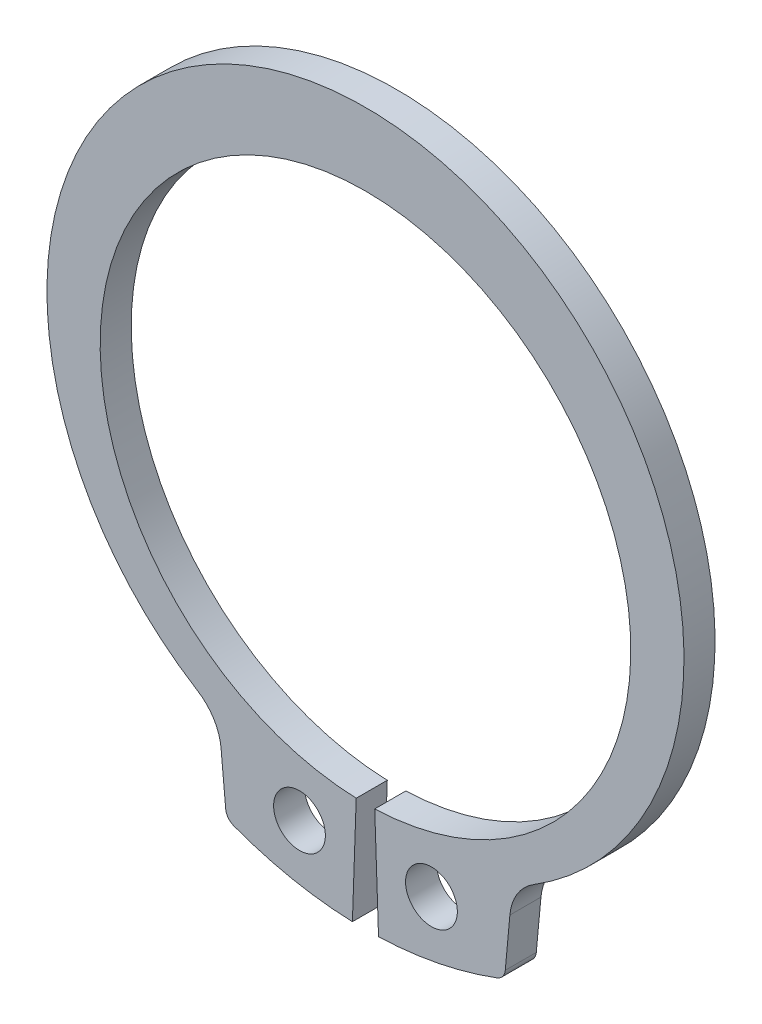
SolidWorks part; units mm, degrees
ref_plane "Front" through (0, 0, 0) normal (0, 0, 1) x (1, 0, 0)
ref_plane "Top" through (0, 0, 0) normal (0, 1, 0) x (1, 0, 0)
ref_plane "Right" through (0, 0, 0) normal (1, 0, 0) x (0, 0, -1)
sketch "Sketch1" plane through (0, 0, 0) normal (0, 0, 1) x (1, 0, 0)
  line L0 (0, 0) -> (-8.8768, -5.125) construction
  line L1 (0, 14.45) -> (0, -14.45) construction
  line L2 (-5.3727, -13.4235) -> (-5.6713, -10.1764) construction
  line L4 (-5.6713, -10.1764) -> (-6.3528, -11.3993) construction
  line L5 (-5.6713, -10.1764) -> (0, 0) construction
  line L6 (0, 10.25) -> (0, 13.05) construction
  line L7 (0, 13.05) -> (0, 11.65) construction
  line L8 (0, -10.25) -> (0, -14.45) construction
  line L9 (-2.9831, -14.1477) -> (0, 0) construction
  line L10 (0, 0) -> (-0.5046, -14.45) construction
  line L11 (-5.3727, -13.4235) -> (0, 0) construction
  line L12 (-5.5852, -11.1124) -> (-6.4883, -9.7116) construction
  line L13 (-6.0368, -10.412) -> (-5.6713, -10.1764) construction
  line L14 (-2.1148, -10.0295) -> (-2.9831, -14.1477) construction
  line L15 (-2.5489, -12.0886) -> (-1.5705, -12.2949) construction
  arc A0 (0, 13.05) -> (-5.6713, -10.1764) centre (0, 0.7444) ccw construction
  circle A2 centre (0, 0) radius 13.05 construction
  arc A3 (-5.3727, -13.4235) -> (-0.5046, -14.45) centre (0, 0) ccw construction
  circle A4 centre (0, 0) radius 10.25 construction
  circle A6 centre (-2.5489, -12.0886) radius 1 construction
  arc A7 (-6.4883, -9.7116) -> (-5.5852, -11.1124) centre (-7.5139, -11.3644) cw construction
  circle A9 centre (0, 0) radius 11 construction
  circle A10 centre (0, 0) radius 10.5 construction
  point P5 (-8.8768, -5.125)
  point P24 (-4.8492, -12.1156)
  point P35 (0, 13.05)
  point P36 (0, 10.25)
  point P37 (0, -10.25)
  point P38 (0, -14.45)
  dimension "Hole Diameter" = 2
  dimension "D10" = 1.9451
  dimension "For OD" = 22
  dimension "ID" = 20.5
  dimension "Max Sec." = 2.8
  dimension "Lug Height" = 4.2
  dimension "D6" = 2
  dimension "D5" = 3.2609
  dimension "D8" = 1.6667
  dimension "D3" = 120
  dimension "D2" = 5
  dimension "D4" = 1.6667
sketch "Sketch2" plane through (0, 0, 0) normal (-1, 0, 0) x (0, 1, 0)
  line L0 (-13.05, 0.6) -> (-13.05, -0.6) construction
  line L1 (13.05, -0.65) -> (13.05, 0.65) construction
  line L2 (0, 0.6) -> (0, -0.6) construction
  line L4 (-13.05, 0) -> (13.05, 0) construction
  point P3 (-13.05, 0)
  point P6 (0, 0)
  point P14 (13.05, 0)
  dimension "Thickness" = 1.2
  dimension "For Groove Width" = 1.3
sketch "Sketch4" plane through (0, 0, 0) normal (0, 0, 1) x (1, 0, 0)
  line L0 (-5.3727, -13.4235) -> (-5.6713, -10.1764) construction
  line L1 (-5.3727, -13.4235) -> (-5.6713, -10.1764)
  line L2 (0, 13.05) -> (0, 10.25)
  line L3 (-0.5046, -14.45) -> (-0.3577, -10.2438)
  line L4 (0, 0) -> (-0.5046, -14.45) construction
  arc A0 (0, 13.05) -> (-5.6713, -10.1764) centre (0, 0.7444) ccw construction
  arc A1 (-5.3727, -13.4235) -> (-0.5046, -14.45) centre (0, 0) ccw construction
  circle A2 centre (-2.5489, -12.0886) radius 1 construction
  arc A4 (0, 13.05) -> (-5.6713, -10.1764) centre (0, 0.7444) ccw
  arc A5 (-5.3727, -13.4235) -> (-0.5046, -14.45) centre (0, 0) ccw
  circle A6 centre (-2.5489, -12.0886) radius 1
  circle A7 centre (0, 0) radius 10.25 construction
  arc A8 (0, 10.25) -> (-0.3577, -10.2438) centre (0, 0) ccw
extrude "Boss-Extrude1" add sketch "Sketch4" along normal mid plane 1.2
fillet "Fillet1" radius 1.9451 1 edges at (-5.6713, -10.1764, 0)
fillet "Fillet2" radius 0.4863 1 edges at (-5.3727, -13.4235, 0)
mirror "Mirror1" about plane through (0, 13.05, 0.6) normal (-1, 0, 0) of bodies 109
sketch "Sketch3" plane through (0, 0, 0.6) normal (0, 0, 1) x (1, 0, 0)
  line L0 (5.7352, -8.4953) -> (6.4896, -9.7108) construction
  line L1 (6.4896, -9.7108) -> (7.7052, -8.9563) construction
  line L2 (0, 13.05) -> (0, 10.25) construction
  circle A0 centre (0, 0) radius 10.25 construction
  arc A1 (6.4896, -9.7108) -> (-6.4896, -9.7108) centre (0, 0.7444) ccw construction
equation "\"D1@Fillet1\" = \"D10@Sketch1\""
equation "\"D1@Fillet2\" = \"D10@Sketch1\" / 4"
equation "\"Thickness@Boss-Extrude1\"  = \"Ring Thickness@Sketch5\""
equation "\"D2@Sketch1\"=\"Hole Diameter@Sketch1\"*2.5"
equation "\"D4@Sketch1\"=\"D2@Sketch1\"/3"
equation "\"D8@Sketch1\"=\"D4@Sketch1\""
